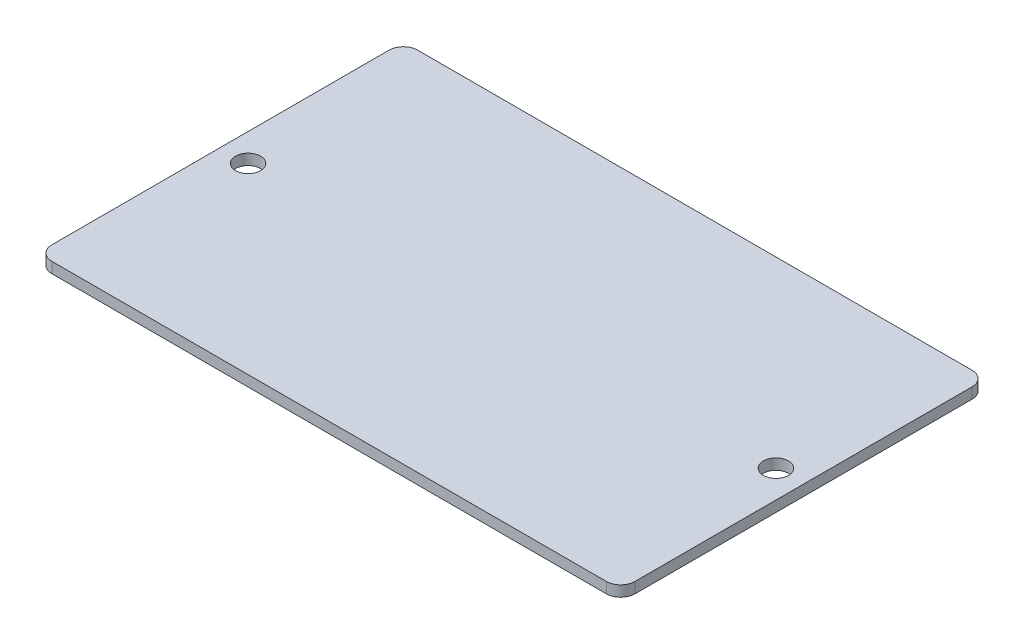
SolidWorks part; units mm, degrees
ref_plane "Front Plane" through (0, 0, 0) normal (0, 0, 1) x (1, 0, 0)
ref_plane "Top Plane" through (0, 0, 0) normal (0, 1, 0) x (1, 0, 0)
ref_plane "Right Plane" through (0, 0, 0) normal (1, 0, 0) x (0, 0, -1)
sketch "Sketch1" plane through (0, 0, 0) normal (0, 1, 0) x (1, 0, 0)
  line L0 (0, 0) -> (81.3, 0)
  line L1 (81.3, 0) -> (81.3, 51)
  line L2 (81.3, 51) -> (0, 51)
  line L3 (0, 51) -> (0, 0)
  point P3 (0, 0)
  dimension "D1" = 81.3
  dimension "D2" = 51
extrude "Boss-Extrude1" add sketch "Sketch1" along normal blind 1.5
fillet "Fillet1" radius 2 4 edges at (81.3, 0.75, -51) (0, 0.75, -51) (81.3, 0.75, 0) (0, 0.75, 0)
sketch "Sketch2" plane through (0, 1.5, 0) normal (0, 1, 0) x (1, 0, 0)
  line L0 (0, 25.5) -> (81.3, 25.5) construction
  line L1 (0, 49) -> (0, 2) construction
  line L2 (81.3, 2) -> (81.3, 49) construction
  line L3 (40.65, 25.5) -> (40.65, 51) construction
  line L4 (79.3, 51) -> (2, 51) construction
  circle A0 centre (3.85, 25.5) radius 1.75
  circle A1 centre (77.45, 25.5) radius 1.75
  point P9 (2.1, 25.5)
  dimension "D1" = 3.5
  dimension "D2" = 3.85
  dimension "D3" = 2.1
extrude "Cut-Extrude1" cut sketch "Sketch2" against normal through all and the other way through all
